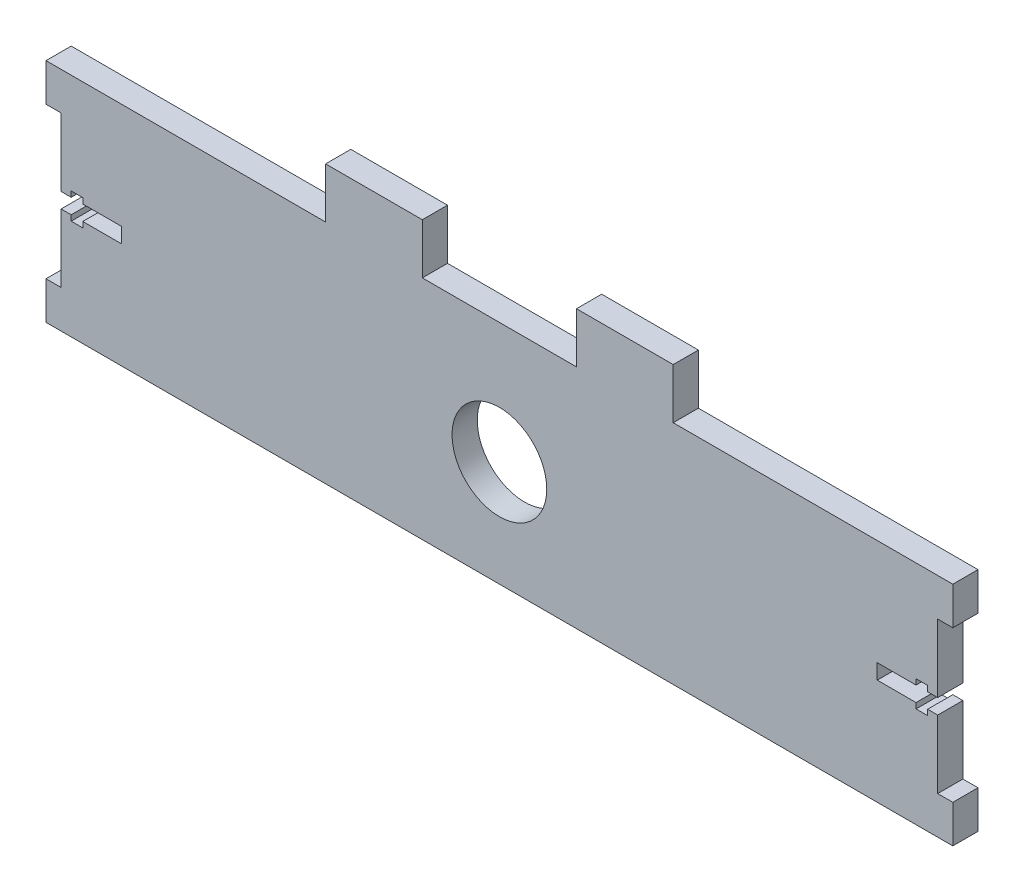
SolidWorks part; units mm, degrees
ref_plane "Plan de face" through (0, 0, 0) normal (0, 0, 1) x (1, 0, 0)
ref_plane "Plan de dessus" through (0, 0, 0) normal (0, 1, 0) x (1, 0, 0)
ref_plane "Plan de droite" through (0, 0, 0) normal (1, 0, 0) x (0, 0, -1)
sketch "Esquisse1" plane through (0, 0, 0) normal (0, 0, 1) x (1, 0, 0)
  line L0 (90, 0) -> (90, 45) construction
  line L1 (90, 45) -> (34.5, 45)
  line L2 (34.5, 45) -> (34.5, 55)
  line L3 (34.5, 55) -> (-34.5, 55) construction
  line L4 (-34.5, 55) -> (-34.5, 45)
  line L5 (-34.5, 45) -> (-90, 45)
  line L6 (-90, 45) -> (-90, 0) construction
  line L7 (-90, 0) -> (90, 0)
  line L8 (0, 0) -> (0, 89.8) construction
  line L9 (-90, 45) -> (-90, 37.5)
  line L10 (-90, 37.5) -> (-87, 37.5)
  line L11 (-87, 37.5) -> (-87, 24)
  line L12 (-87, 24) -> (-85, 24)
  line L13 (-85, 24) -> (-85, 25.1)
  line L14 (-85, 25.1) -> (-82.7, 25.1)
  line L15 (-82.7, 25.1) -> (-82.7, 24)
  line L16 (-82.7, 24) -> (-75, 24)
  line L17 (-75, 24) -> (-75, 21)
  line L18 (-75, 21) -> (-82.7, 21)
  line L19 (-82.7, 21) -> (-82.7, 19.9)
  line L20 (-82.7, 19.9) -> (-85, 19.9)
  line L21 (-85, 19.9) -> (-85, 21)
  line L22 (-85, 21) -> (-87, 21)
  line L23 (-87, 21) -> (-87, 7.5)
  line L24 (-87, 7.5) -> (-90, 7.5)
  line L25 (-90, 7.5) -> (-90, 0)
  line L26 (-90, 22.5) -> (-42.3783, 22.5) construction
  line L27 (90, 22.5) -> (42.3783, 22.5) construction
  line L28 (90, 45) -> (90, 0) construction
  line L29 (90, 7.5) -> (90, 0)
  line L30 (87, 7.5) -> (90, 7.5)
  line L31 (87, 21) -> (87, 7.5)
  line L32 (85, 21) -> (87, 21)
  line L33 (85, 19.9) -> (85, 21)
  line L34 (82.7, 19.9) -> (85, 19.9)
  line L35 (82.7, 21) -> (82.7, 19.9)
  line L36 (75, 21) -> (82.7, 21)
  line L37 (75, 24) -> (75, 21)
  line L38 (82.7, 24) -> (75, 24)
  line L39 (82.7, 25.1) -> (82.7, 24)
  line L40 (85, 25.1) -> (82.7, 25.1)
  line L41 (85, 24) -> (85, 25.1)
  line L42 (87, 24) -> (85, 24)
  line L43 (87, 37.5) -> (87, 24)
  line L44 (90, 37.5) -> (87, 37.5)
  line L45 (90, 45) -> (90, 37.5)
  line L46 (-17.7718, 33) -> (6.3703, 33) construction
  line L47 (-34.5, 55) -> (-15.3, 55)
  line L48 (-15.3, 55) -> (-15.3, 45)
  line L49 (-15.3, 45) -> (15.3, 45)
  line L50 (15.3, 45) -> (15.3, 55)
  line L51 (15.3, 55) -> (34.5, 55)
  circle A0 centre (0, 21) radius 12 construction
  circle A1 centre (0, 21) radius 9.4
  point P36 (-88.5, 7.5)
  dimension "D12" = 24
  dimension "D15" = 18.8
  dimension "D2" = 180
  dimension "D3" = 69
  dimension "D4" = 10
  dimension "D5" = 30
  dimension "D6" = 3
  dimension "D7" = 15
  dimension "D8" = 2.3
  dimension "D9" = 5.2
  dimension "D10" = 3
  dimension "D11" = 2
  dimension "D13" = 22
  dimension "D14" = 45
  dimension "D16" = 19.2
  dimension "D17" = 19.2
  dimension "D18" = 30.6
  dimension "D19" = 21
extrude "Boss.-Extru.1" add sketch "Esquisse1" along normal blind 5
